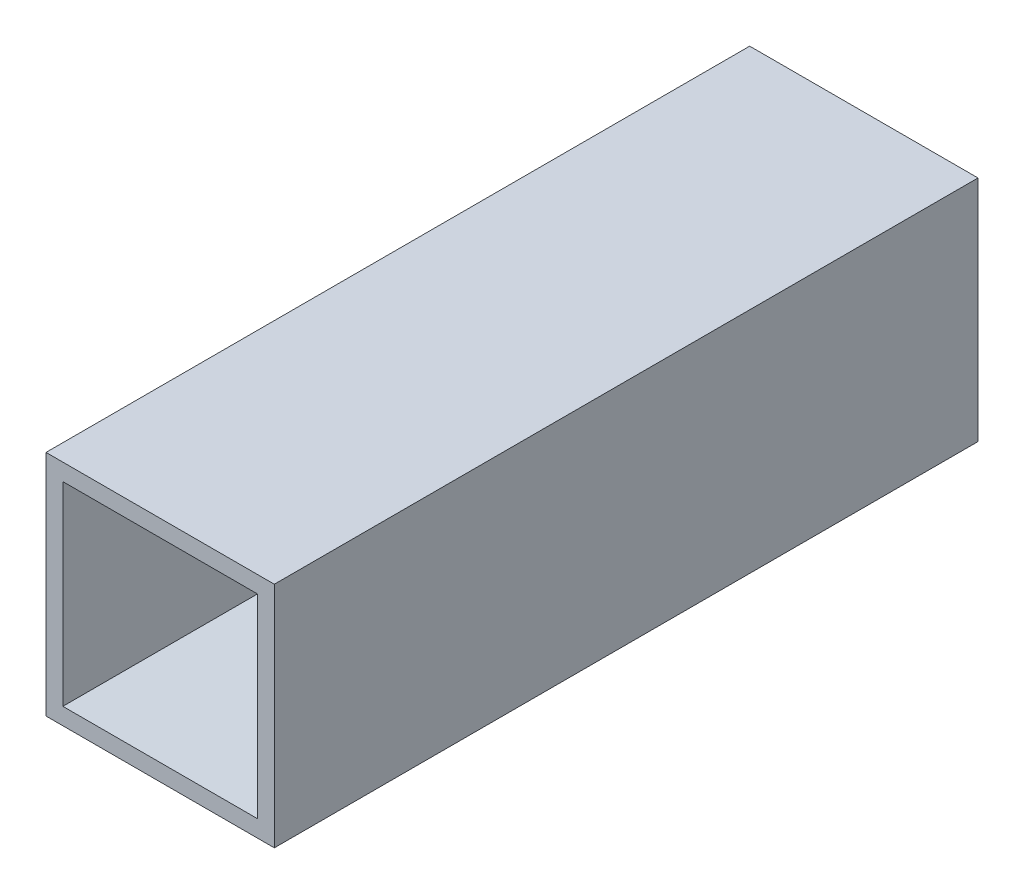
SolidWorks part; units mm, degrees
ref_plane "Front Plane" through (0, 0, 0) normal (0, 0, 1) x (1, 0, 0)
ref_plane "Top Plane" through (0, 0, 0) normal (0, 1, 0) x (1, 0, 0)
ref_plane "Right Plane" through (0, 0, 0) normal (1, 0, 0) x (0, 0, -1)
sketch "Sketch1" plane through (0, 0, 0) normal (0, 0, 1) x (1, 0, 0)
  line L1 (0, 0) -> (305, 0)
  line L2 (0, 0) -> (0, 305)
  line L3 (0, 305) -> (305, 305)
  line L4 (305, 0) -> (305, 305)
  dimension "D1" = 305
  dimension "D2" = 305
extrude "Boss-Extrude2" add sketch "Sketch1" along normal blind 874
sketch "Sketch2" plane through (0, 0, 0) normal (0, 0, -1) x (-1, 0, 0)
  line L1 (-242.5, 242.5) -> (-62.5, 242.5)
  line L2 (-242.5, 242.5) -> (-242.5, 62.5)
  line L3 (-242.5, 62.5) -> (-62.5, 62.5)
  line L4 (-62.5, 242.5) -> (-62.5, 62.5)
  line L6 (0, 305) -> (0, 0) construction
  line L7 (-305, 305) -> (0, 305) construction
  dimension "D1" = 180
  dimension "D2" = 180
  dimension "D3" = 62.5
  dimension "D4" = 62.5
sketch "Sketch3" plane through (0, 0, 0) normal (-1, 0, 0) x (0, 0, 1)
  line L0 (874, 305) -> (874, 0) construction
  line L1 (824, 202.5) -> (724, 202.5)
  line L2 (824, 202.5) -> (824, 102.5)
  line L3 (824, 102.5) -> (724, 102.5)
  line L4 (724, 202.5) -> (724, 102.5)
  line L5 (874, 0) -> (0, 0) construction
  dimension "D1" = 100
  dimension "D2" = 100
  dimension "D3" = 50
  dimension "D4" = 102.5
extrude "Boss-Extrude4" add sketch "Sketch3" along normal blind 100
sketch "Sketch5" plane through (0, 102.5, 0) normal (0, -1, 0) x (1, 0, 0)
  line L0 (-100, 824) -> (0, 824)
  line L1 (0, 824) -> (-100, 724)
  line L2 (-100, 724) -> (-100, 824)
extrude "Cut-Extrude3" cut sketch "Sketch5" against normal blind 100
sketch "Sketch6" plane through (0, 0, 874) normal (0, 0, 1) x (1, 0, 0)
  line L0 (305, 305) -> (0, 305) construction
  line L1 (22.5, 282.5) -> (282.5, 282.5)
  line L2 (22.5, 282.5) -> (22.5, 22.5)
  line L3 (22.5, 22.5) -> (282.5, 22.5)
  line L4 (282.5, 282.5) -> (282.5, 22.5)
  line L5 (305, 0) -> (305, 305) construction
  dimension "D1" = 22.5
  dimension "D2" = 260
  dimension "D3" = 260
  dimension "D4" = 22.5
loft "Cut-Loft2" cut profiles "Sketch2", "Sketch6"
sketch "Sketch8" plane through (0, 0, 0) normal (0, 0, -1) x (-1, 0, 0)
  line L0 (-305, 305) -> (0, 305)
  line L1 (0, 305) -> (0, 0)
  line L2 (0, 0) -> (-305, 0)
  line L3 (-305, 0) -> (-305, 305)
extrude "Boss-Extrude5" add sketch "Sketch8" along normal blind 66
